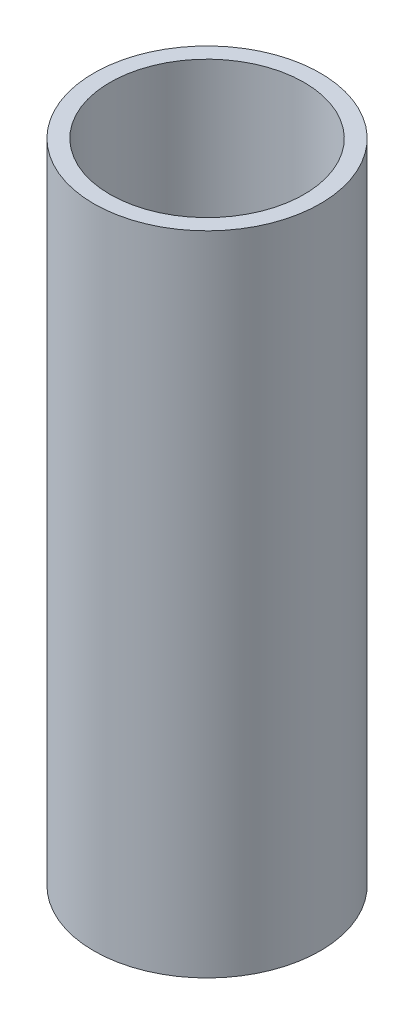
SolidWorks part; units mm, degrees
ref_plane "Front Plane" through (0, 0, 0) normal (0, 0, 1) x (1, 0, 0)
ref_plane "Top Plane" through (0, 0, 0) normal (0, 1, 0) x (1, 0, 0)
ref_plane "Right Plane" through (0, 0, 0) normal (1, 0, 0) x (0, 0, -1)
sketch "Sketch1" plane through (0, 0, 0) normal (0, 1, 0) x (1, 0, 0)
  circle A0 centre (0, 0) radius 1.5
  circle A1 centre (0, 0) radius 1.75
  dimension "D1" = 3
  dimension "D2" = 3.5
extrude "Boss-Extrude1" add sketch "Sketch1" along normal blind 10
